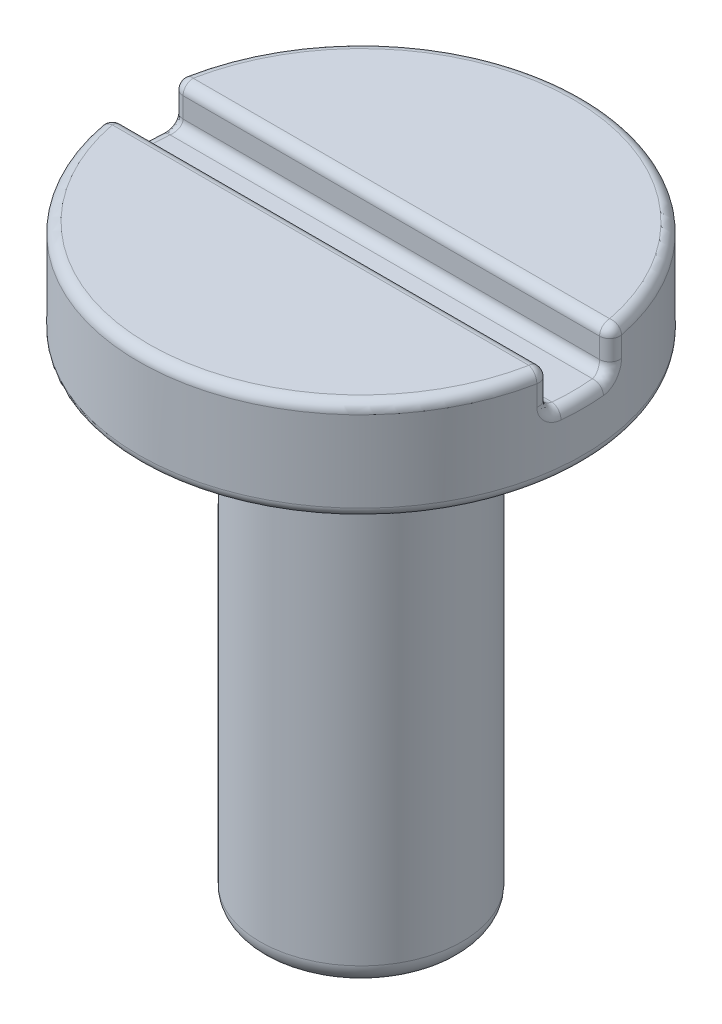
SolidWorks part; units mm, degrees
ref_plane "Front Plane" through (0, 0, 0) normal (0, 0, 1) x (1, 0, 0)
ref_plane "Top Plane" through (0, 0, 0) normal (0, 1, 0) x (1, 0, 0)
ref_plane "Right Plane" through (0, 0, 0) normal (1, 0, 0) x (0, 0, -1)
sketch "Sketch1" plane through (0, 0, 0) normal (0, 1, 0) x (1, 0, 0)
  circle A0 centre (0, 0) radius 1.1
  dimension "D1" = 2.2
extrude "Boss-Extrude1" add sketch "Sketch1" along normal blind 0.5
sketch "Sketch2" plane through (0, 0.5, 0) normal (0, 1, 0) x (1, 0, 0)
  line L0 (-0.275, 0) -> (0.275, 0) construction
  line L1 (-1.3947, 0.15) -> (1.4497, 0.15)
  line L2 (-1.3947, 0.15) -> (-1.3947, -0.15)
  line L3 (-1.3947, -0.15) -> (1.4497, -0.15)
  line L4 (1.4497, 0.15) -> (1.4497, -0.15)
  dimension "D1" = 0.3
  dimension "D2" = 0.15
extrude "Cut-Extrude1" cut sketch "Sketch2" against normal blind 0.2
fillet "Fillet1" radius 0.05 13 edges at (1.0897, 0.4, -0.15) (-1.0897, 0.4, -0.15) (0, 0.3, 0.15) (0, 0.3, -0.15) (1.0897, 0.4, 0.15) (-1.0897, 0.4, 0.15) (0, 0, 1.1) (0, 0.5, 1.1) (0, 0.5, -1.1) (0, 0.5, 0.15) (0, 0.5, -0.15) (1.1, 0.3, 0) (-1.1, 0.3, 0)
sketch "Sketch3" plane through (0, 0, 0) normal (0, -1, 0) x (1, 0, 0)
  circle A0 centre (0, 0) radius 0.5
  dimension "D1" = 1
extrude "Boss-Extrude2" add sketch "Sketch3" along normal blind 2.5
chamfer "Chamfer1" distance 0.1 angle 65 1 edges at (0, -2.5, -0.5)
fillet "Fillet2" radius 0.1 2 edges at (0, -2.5, -0.2855) (0, -2.4, -0.5)
